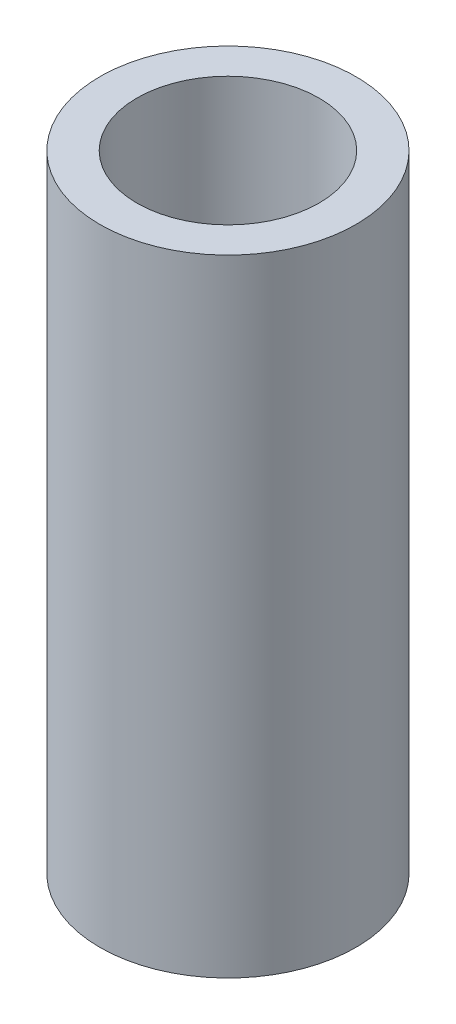
SolidWorks part; units mm, degrees
material "ABS"
ref_plane "Front" through (0, 0, 0) normal (0, 0, 1) x (1, 0, 0)
ref_plane "Top" through (0, 0, 0) normal (0, 1, 0) x (1, 0, 0)
ref_plane "Right" through (0, 0, 0) normal (1, 0, 0) x (0, 0, -1)
sketch "Sketch1" plane through (0, 0, 0) normal (0, 1, 0) x (1, 0, 0)
  circle A0 centre (0, 0) radius 2.25
  circle A1 centre (0, 0) radius 1.6
  dimension "D1" = 4.5
  dimension "D2" = 3.2
extrude "Boss-Extrude1" add sketch "Sketch1" along normal mid plane 11
